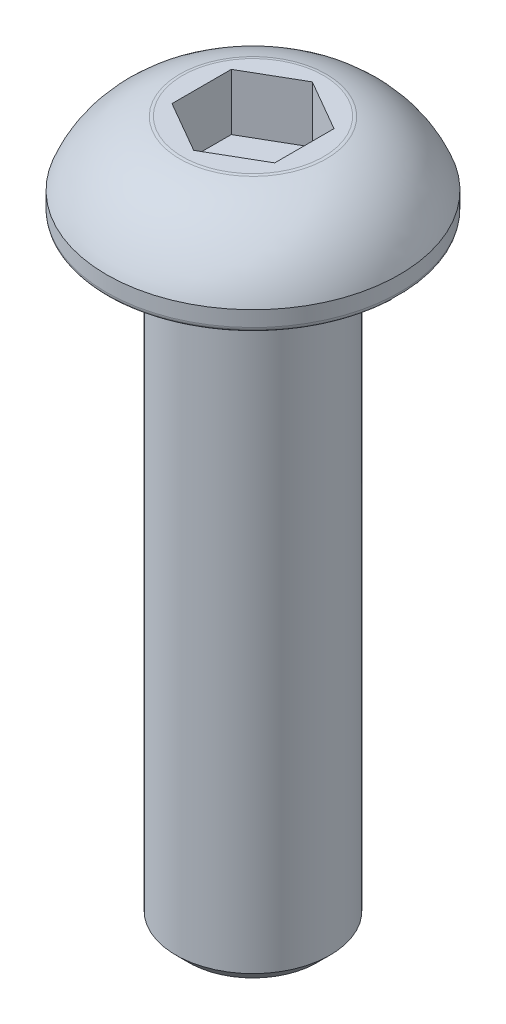
SolidWorks part; units mm, degrees
material "ASTM A36 Steel"
ref_plane "Front Plane" through (0, 0, 0) normal (0, 0, 1) x (1, 0, 0)
ref_plane "Top Plane" through (0, 0, 0) normal (0, 1, 0) x (1, 0, 0)
ref_plane "Right Plane" through (0, 0, 0) normal (1, 0, 0) x (0, 0, -1)
sketch "Sketch1" plane through (0, 0, 0) normal (0, 0, 1) x (1, 0, 0)
  line L7 (-1.5, -0.1) -> (-1.5, -11.75)
  line L8 (-1.25, -12) -> (0, -12)
  line L9 (0, -12) -> (0, 1.65)
  line L10 (-1.6, 0) -> (-2.75, 0)
  line L11 (-2.85, 0.1) -> (-2.85, 0.4)
  line L12 (-1.3725, 1.65) -> (0, 1.65)
  line L13 (-1.5, -11.75) -> (-1.25, -12)
  arc A0 (-2.85, 0.4) -> (-1.4287, 1.6436) centre (-0.9784, -0.3051) cw
  arc A3 (-2.75, 0) -> (-2.85, 0.1) centre (-2.75, 0.1) cw
  arc A4 (-1.4287, 1.6436) -> (-1.3725, 1.65) centre (-1.3725, 1.4) cw
  arc A5 (-1.5, -0.1) -> (-1.6, 0) centre (-1.6, -0.1) ccw
  point P1 (-1.5, -12)
  point P21 (-1.4, 1.65)
  point P24 (-1.5, 0)
  dimension "D1" = 1.5
  dimension "D7" = 2
  dimension "D8" = 0.1
  dimension "D9" = 0.25
  dimension "D10" = 0.1
  dimension "D2" = 2.85
  dimension "D4" = 1.4
  dimension "D5" = 1.65
  dimension "D6" = 0.4
  dimension "D11" = 12
revolve "Revolve1" add sketch "Sketch1" angle 360 about L9
sketch "Sketch2" plane through (0, 1.65, 0) normal (0, 1, 0) x (1, 0, 0)
  line L1 (-1, 0.5774) -> (-1, -0.5774)
  line L2 (-1, -0.5774) -> (0, -1.1547)
  line L3 (0, -1.1547) -> (1, -0.5774)
  line L4 (1, -0.5774) -> (1, 0.5774)
  line L5 (1, 0.5774) -> (0, 1.1547)
  line L6 (0, 1.1547) -> (-1, 0.5774)
  circle A0 centre (0, 0) radius 1 construction
  dimension "D1" = 2
extrude "Cut-Extrude1" cut sketch "Sketch2" against normal blind 1.1
